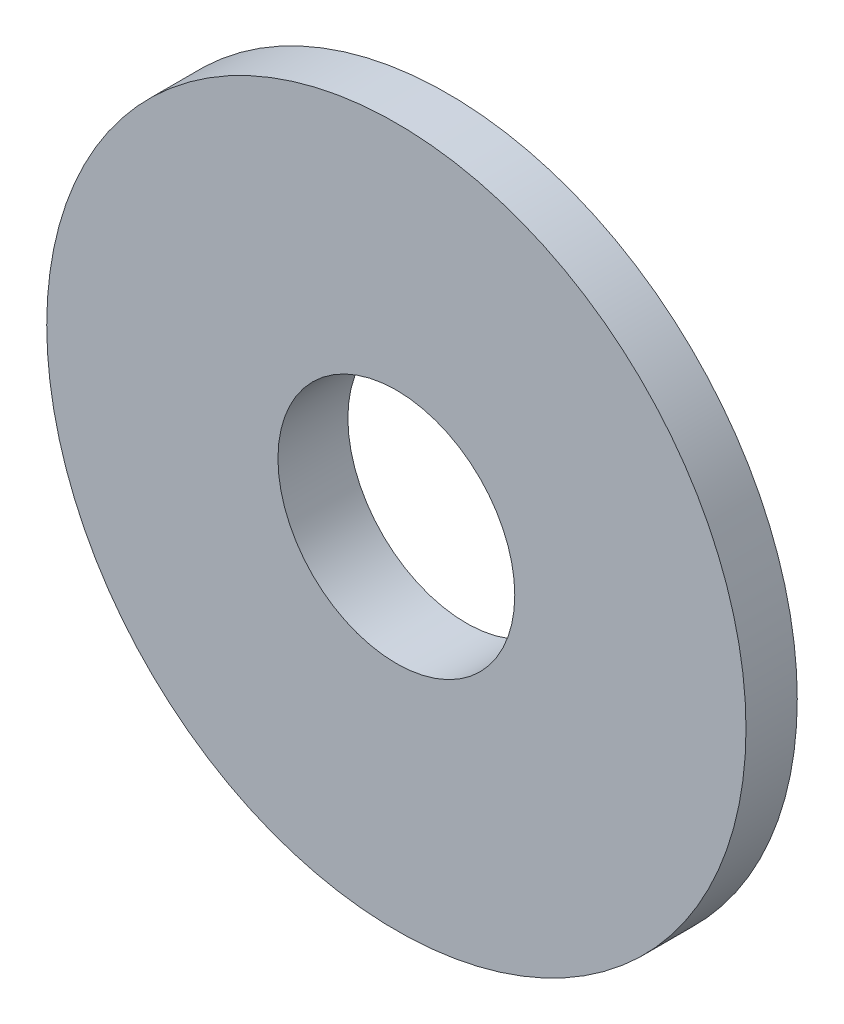
SolidWorks part; units mm, degrees
ref_plane "Front Plane" through (0, 0, 0) normal (0, 0, 1) x (1, 0, 0)
ref_plane "Top Plane" through (0, 0, 0) normal (0, 1, 0) x (1, 0, 0)
ref_plane "Right Plane" through (0, 0, 0) normal (1, 0, 0) x (0, 0, -1)
sketch "Sketch1" plane through (0, 0, 0) normal (0, 0, 1) x (1, 0, 0)
  circle A0 centre (0, 0) radius 9.525
  circle A1 centre (0, 0) radius 3.2258
extrude "Extrude1" add sketch "Sketch1" along normal blind 1.397
sketch "Sketch2" plane through (0, 0, 0) normal (0, 0, -1) x (-1, 0, 0)
  circle A0 centre (0, 0) radius 3.2258
  circle A1 centre (0, 0) radius 4.7625
extrude "Extrude2" add sketch "Sketch2" along normal blind 0.508
